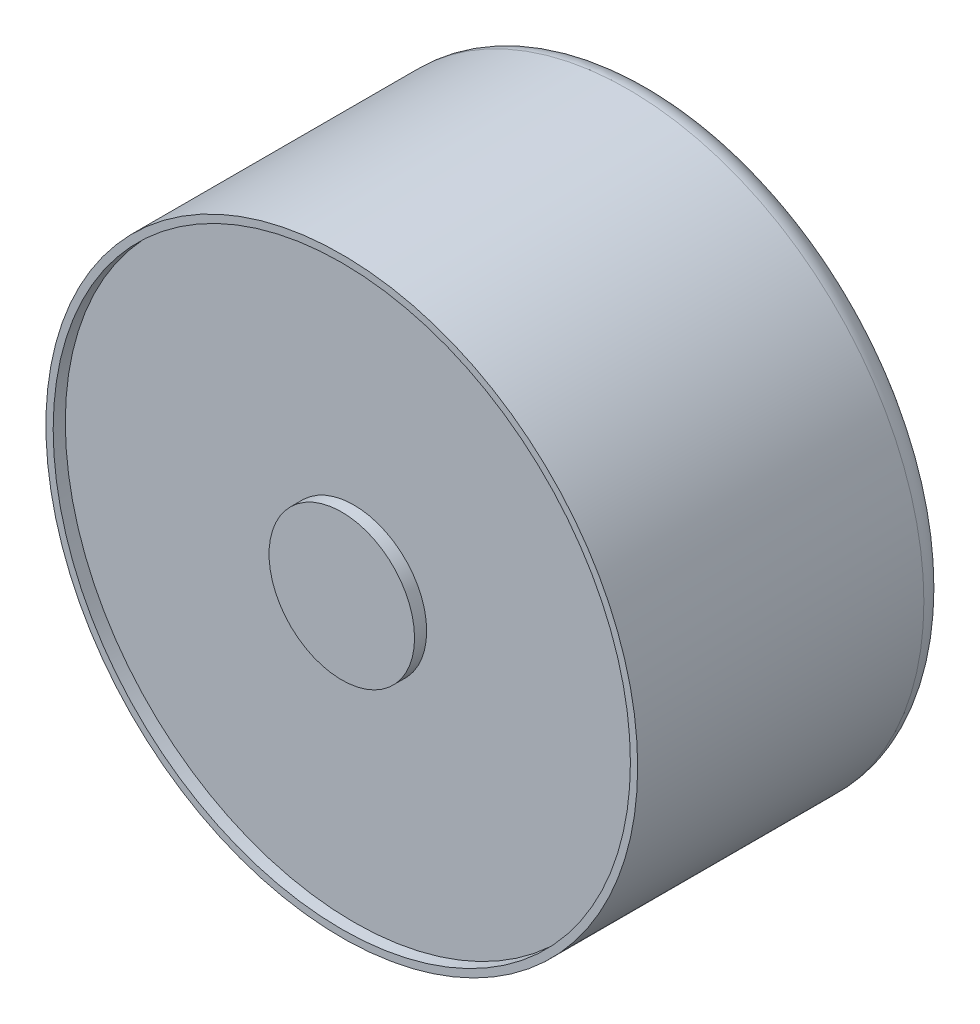
SolidWorks part; units mm, degrees
ref_plane "Front Plane" through (0, 0, 0) normal (0, 0, 1) x (1, 0, 0)
ref_plane "Top Plane" through (0, 0, 0) normal (0, 1, 0) x (1, 0, 0)
ref_plane "Right Plane" through (0, 0, 0) normal (1, 0, 0) x (0, 0, -1)
sketch "Sketch1" plane through (0, 0, 0) normal (0, 1, 0) x (1, 0, 0)
  line L0 (0, 0) -> (0, 17.0776) construction
  line L1 (0, 0) -> (3, 0)
  line L2 (3, 0) -> (3, 0.5)
  line L3 (3, 0.5) -> (11.9, 0.5)
  line L4 (11.9, 0.5) -> (11.9, 0)
  line L5 (11.9, 0) -> (12.2, 0)
  line L6 (12.2, 0) -> (12.2, 11.8)
  line L7 (11.2, 12.8) -> (3, 12.8)
  line L8 (3, 12.8) -> (3, 13.3)
  line L9 (3, 13.3) -> (0, 13.3)
  line L10 (0, 13.3) -> (0, 0)
  arc A0 (12.2, 11.8) -> (11.2, 12.8) centre (11.2, 11.8) ccw
  point P14 (12.2, 12.8)
  dimension "D7" = 1
  dimension "D1" = 12.8
  dimension "D2" = 12.2
  dimension "D3" = 0.5
  dimension "D4" = 3
  dimension "D5" = 0.3
  dimension "D6" = 0.5
revolve "Revolve1" add sketch "Sketch1" angle 360 about L0
sketch "Sketch2" plane through (0, 0, -13.3) normal (0, 0, -1) x (-1, 0, 0)
  circle A0 centre (0, 0) radius 1
  point P2 (0, 0)
  dimension "D1" = 2
extrude "Boss-Extrude1" add sketch "Sketch2" along normal blind 6
hole_wizard "M1.6 Clearance Hole1" positions "Sketch3" profile "Sketch4" hole size "M1.6" standard "ANSI Metric"
sketch "Sketch3" plane through (0, 0, -12.8) normal (0, 0, -1) x (-1, 0, 0)
  point P0 (0, 8.25)
  dimension "D1" = 8.25
sketch "Sketch4" plane through (0, 8.25, -12.8) normal (1, 0, 0) x (0, 1, 0)
  line L0 (0, 0) -> (0, 3.6009)
  line L1 (0, 3.6009) -> (1, 3)
  line L2 (1, 3) -> (1, 0)
  line L5 (1, 0) -> (0, 0)
  line L10 (0, 3.6009) -> (-1, 3) construction
  line L11 (0, -6.35) -> (0, 107.95) construction
  dimension "Hole Dia." = 2
  dimension "Hole Depth" = 3
  dimension "Drill Angle" = 118
pattern_circular "CirPattern1" count 6 over 360 about axis through (0, 0, 0) along (0, 0, 1) of "M1.6 Clearance Hole1"
